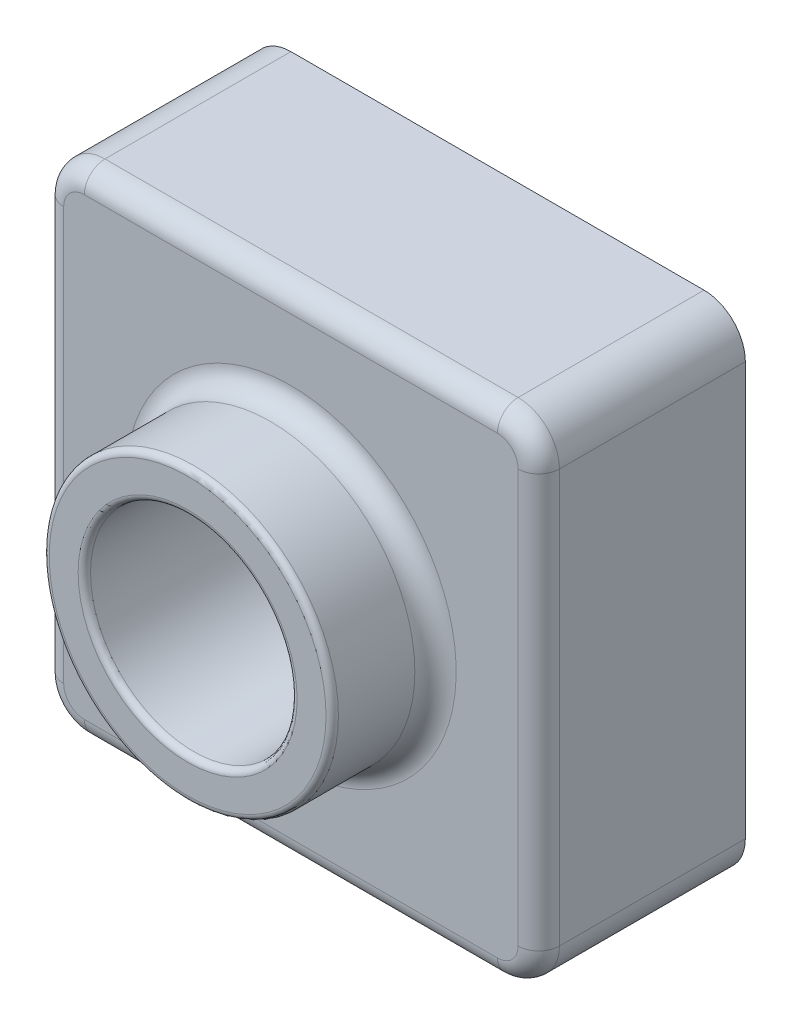
SolidWorks part; units mm, degrees
ref_plane "Front" through (0, 0, 0) normal (0, 0, 1) x (1, 0, 0)
ref_plane "Top" through (0, 0, 0) normal (0, 1, 0) x (1, 0, 0)
ref_plane "Right" through (0, 0, 0) normal (1, 0, 0) x (0, 0, -1)
sketch "Sketch1" plane through (0, 0, 0) normal (0, 0, 1) x (1, 0, 0)
  line L0 (0, 148.1757) -> (0, -140.8784) construction
  line L1 (129.3243, 0) -> (-124.4595, 0) construction
  line L2 (0, 0) -> (0, 120)
  line L3 (0, 120) -> (120, 120)
  line L4 (120, 120) -> (120, 0)
  line L5 (120, 0) -> (0, 0)
  dimension "D1" = 120
  dimension "D2" = 120
extrude "Boss-Extrude1" add sketch "Sketch1" along normal blind 50
sketch "Sketch2" plane through (0, 0, 50) normal (0, 0, 1) x (1, 0, 0)
  line L0 (120, 120) -> (0, 120) construction
  line L2 (0, 120) -> (0, 0) construction
  circle A0 centre (60, 60) radius 35
  point P6 (0, 58.2281)
  point P7 (0, 60)
  dimension "D3" = 70
  dimension "D1" = 60
  dimension "D2" = 60
extrude "Boss-Extrude2" add sketch "Sketch2" along normal blind 25
sketch "Sketch3" plane through (0, 0, 75) normal (0, 0, 1) x (1, 0, 0)
  circle A1 centre (60, 60) radius 25
  dimension "D1" = 50
extrude "Cut-Extrude1" cut sketch "Sketch3" against normal through all
fillet "Fillet1" radius 10 4 edges at (0, 0, 25) (120, 120, 25) (0, 120, 25) (120, 0, 25)
fillet "Fillet2" radius 1.5 2 edges at (95, 60, 75) (85, 60, 75)
fillet "Fillet3" radius 5 9 edges at (2.9289, 117.0711, 50) (60, 120, 50) (117.0711, 117.0711, 50) (120, 60, 50) (117.0711, 2.9289, 50) (60, 0, 50) (2.9289, 2.9289, 50) (0, 60, 50) (95, 60, 50)
shell "Shell1" thickness 2
